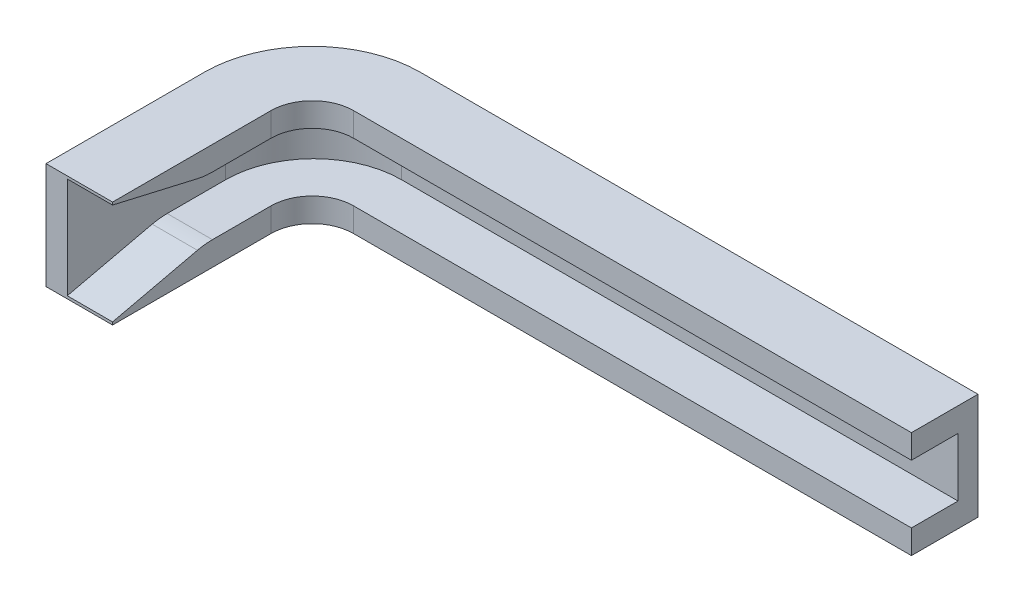
SolidWorks part; units mm, degrees
ref_plane "Front Plane" through (0, 0, 0) normal (0, 0, 1) x (1, 0, 0)
ref_plane "Top Plane" through (0, 0, 0) normal (0, 1, 0) x (1, 0, 0)
ref_plane "Right Plane" through (0, 0, 0) normal (1, 0, 0) x (0, 0, -1)
sketch "Sketch1" plane through (0, 0, 0) normal (0, 0, 1) x (1, 0, 0)
  line L1 (0, 0) -> (50, 0)
  line L2 (0, 0) -> (0, 8)
  line L3 (0, 8) -> (50, 8)
  line L4 (50, 0) -> (50, 8)
  dimension "D1" = 50
  dimension "D2" = 8
extrude "Boss-Extrude1" add sketch "Sketch1" along normal blind 20
sketch "Sketch2" plane through (0, 0, 20) normal (0, 0, 1) x (1, 0, 0)
  line L0 (50, 0) -> (50, 8) construction
  line L1 (1.6, 6.2037) -> (50, 6.2037)
  line L2 (1.6, 6.2037) -> (1.6, 1.8037)
  line L3 (1.6, 1.8037) -> (50, 1.8037)
  line L4 (50, 6.2037) -> (50, 1.8037)
  line L5 (50, 8) -> (0, 8) construction
  line L6 (0, 8) -> (0, 0) construction
  point P8 (0, 4)
  dimension "D1" = 1.7963
  dimension "D2" = 4.4
  dimension "D3" = 1.6
extrude "Cut-Extrude1" cut sketch "Sketch2" against normal blind 18.5
sketch "Sketch3" plane through (0, 0, 0) normal (0, -1, 0) x (-1, 0, 0)
  line L0 (0, -20) -> (-50, -20) construction
  line L1 (-5, -20) -> (-50, -20)
  line L2 (-5, -20) -> (-5, -5)
  line L3 (-5, -5) -> (-50, -5)
  line L4 (-50, -20) -> (-50, -5)
  line L5 (-50, -20) -> (-50, 0) construction
  line L6 (0, -20) -> (0, 0) construction
  line L7 (0, 0) -> (-50, 0) construction
  dimension "D1" = 5
  dimension "D2" = 5
extrude "Cut-Extrude2" cut sketch "Sketch3" against normal blind 18
fillet "Fillet1" radius 6.6 1 edges at (1.6, 4.0037, 1.5)
fillet "Fillet2" radius 8.1 1 edges at (0, 4, 0)
fillet "Fillet3" radius 3.1 2 edges at (5, 0.9018, 5) (5, 7.1018, 5)
chamfer "Chamfer1" distance 1.6 angle 77 2 edges at (3.3, 1.8037, 20) (3.3, 6.2037, 20)
fillet "Fillet4" radius 5 2 edges at (3.3, 1.8037, 13.0696) (3.3, 6.2037, 13.0696)
